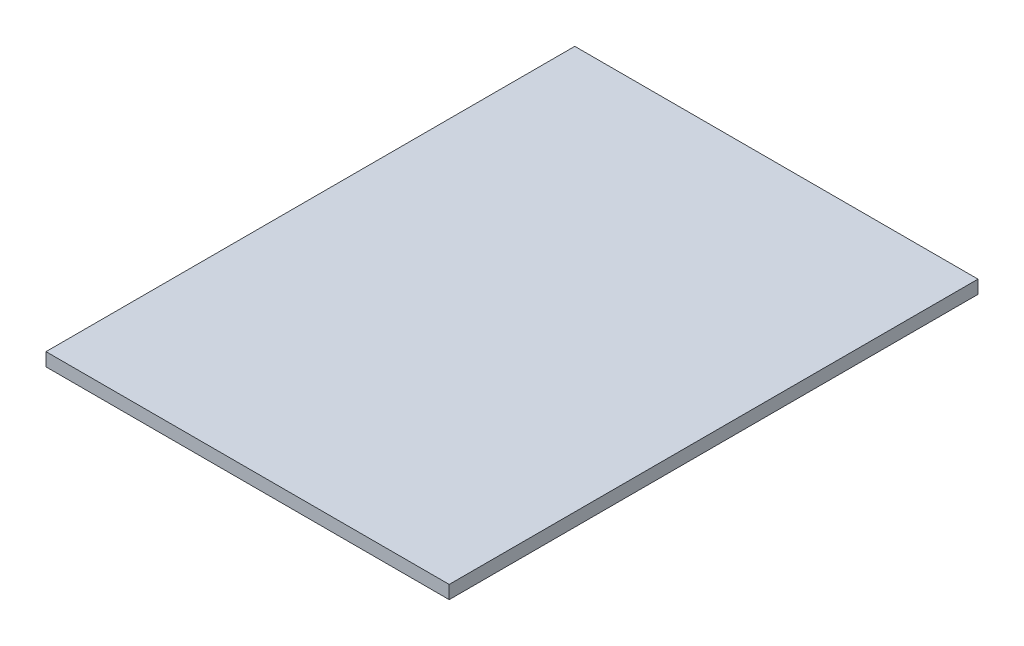
SolidWorks part; units mm, degrees
ref_plane "Ebene vorne" through (0, 0, 0) normal (0, 0, 1) x (1, 0, 0)
ref_plane "Ebene oben" through (0, 0, 0) normal (0, 1, 0) x (1, 0, 0)
ref_plane "Ebene rechts" through (0, 0, 0) normal (1, 0, 0) x (0, 0, -1)
sketch "Skizze1" plane through (0, 0, 0) normal (0, 1, 0) x (1, 0, 0)
  line L1 (-30.5, 40) -> (30.5, 40)
  line L2 (-30.5, 40) -> (-30.5, -40)
  line L3 (-30.5, -40) -> (30.5, -40)
  line L4 (30.5, 40) -> (30.5, -40)
  line L5 (-30.5, 40) -> (30.5, -40) construction
  line L6 (-30.5, -40) -> (30.5, 40) construction
  point P0 (0, 0)
  dimension "D1" = 80
  dimension "D2" = 61
extrude "Aufsatz-Linear austragen1" add sketch "Skizze1" along normal blind 2
